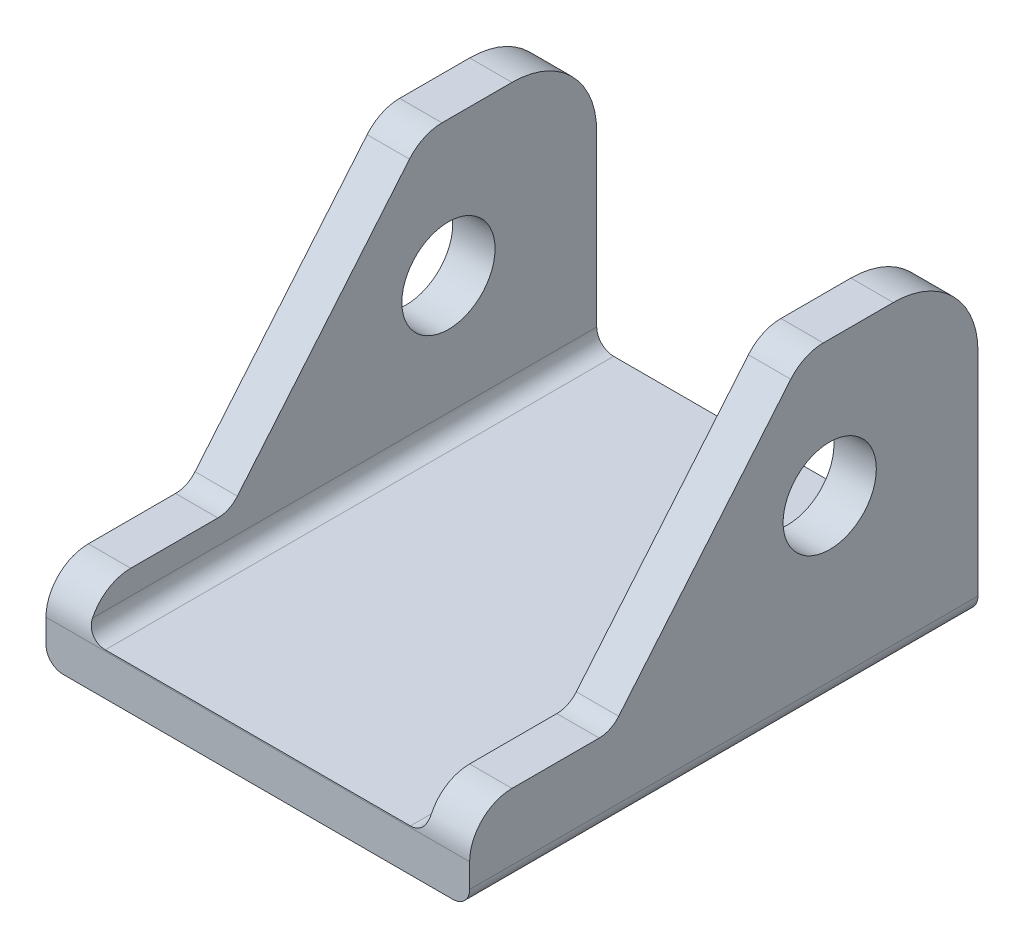
SolidWorks part; units mm, degrees
material "1.0490 (S275N)"
ref_plane "Front Plane" through (0, 0, 0) normal (0, 0, 1) x (1, 0, 0)
ref_plane "Top Plane" through (0, 0, 0) normal (0, 1, 0) x (1, 0, 0)
ref_plane "Right Plane" through (0, 0, 0) normal (1, 0, 0) x (0, 0, -1)
sketch "Sketch1" plane through (0, 0, 0) normal (0, 0, 1) x (1, 0, 0)
  line L0 (-86.9252, -8.2481) -> (-50.9252, -8.2481)
  line L1 (-88.9252, -6.2481) -> (-88.9252, 23.7519)
  line L2 (-48.9252, -6.2481) -> (-48.9252, 23.7519)
  line L3 (-93.9252, -11.2481) -> (-93.9252, 23.7519)
  line L4 (-91.9252, -13.2481) -> (-45.9252, -13.2481)
  line L5 (-43.9252, -11.2481) -> (-43.9252, 23.7519)
  line L6 (-88.9252, -8.2481) -> (-48.9252, -8.2481) construction
  line L7 (-88.9252, -8.2481) -> (-88.9252, 23.7519) construction
  line L8 (-48.9252, -8.2481) -> (-48.9252, 23.7519) construction
  line L9 (-93.9252, -13.2481) -> (-43.9252, -13.2481) construction
  line L10 (-43.9252, -13.2481) -> (-43.9252, 23.7519) construction
  line L11 (-93.9252, -13.2481) -> (-93.9252, 23.7519) construction
  line L12 (-93.9252, 23.7519) -> (-88.9252, 23.7519)
  line L13 (-48.9252, 23.7519) -> (-43.9252, 23.7519)
  arc A0 (-86.9252, -8.2481) -> (-88.9252, -6.2481) centre (-86.9252, -6.2481) cw
  arc A1 (-50.9252, -8.2481) -> (-48.9252, -6.2481) centre (-50.9252, -6.2481) ccw
  arc A2 (-45.9252, -13.2481) -> (-43.9252, -11.2481) centre (-45.9252, -11.2481) ccw
  arc A3 (-91.9252, -13.2481) -> (-93.9252, -11.2481) centre (-91.9252, -11.2481) cw
  dimension "D2" = 2
  dimension "D3" = 2
  dimension "D4" = 2
  dimension "D5" = 2
  dimension "D1" = 5
extrude "Boss-Extrude1" add sketch "Sketch1" along normal blind 60
hole_wizard "M10 Clearance Slot2" positions "Sketch4" profile "Sketch5" size "M10" standard "ISO" slot yes end condition through all
sketch "Sketch4" plane through (-43.9252, 0, 0) normal (1, 0, 0) x (0, 0, -1)
  line L0 (-60, -13.2481) -> (0, -13.2481) construction
  line L1 (0, -11.2481) -> (0, 23.7519) construction
  point P0 (-17.5, 7.7519)
  dimension "D1" = 21
  dimension "D2" = 17.5
sketch "Sketch5" plane through (-43.9252, 7.7519, 17.5) normal (0, 1, 0) x (0, 0, -1)
  line L0 (0, 0) -> (0, 50)
  line L1 (0, 50) -> (5.5, 50)
  line L2 (5.5, 50) -> (5.5, 0)
  line L5 (5.5, 0) -> (0, 0)
  line L11 (0, -6.35) -> (0, 107.95) construction
  dimension "Thru Hole Dia." = 11
  dimension "Thru Hole Depth" = 50
fillet "Fillet3" radius 10 1 edges at (-46.4252, 23.7519, 0)
fillet "Fillet4" radius 10 1 edges at (-91.4252, 23.7519, 0)
fillet "Fillet5" radius 10 1 edges at (-91.4252, 23.7519, 60)
fillet "Fillet6" radius 10 1 edges at (-46.4252, 23.7519, 60)
extrude "Cut-Extrude7" cut sketch "Sketch14" against normal through all and the other way through all
sketch "Sketch14" plane through (-93.9252, 454.8394, 464.6797) normal (-1, 0, 0) x (0, 1, 0)
  line L0 (-432.8802, 442.58) -> (-457.1734, 422.2676)
  line L2 (-458.249, 419.9661) -> (-458.249, 409.6797)
  line L4 (-431.0875, 446.4158) -> (-431.0875, 454.6797)
  line L5 (-463.249, 404.6797) -> (-466.0875, 404.6797)
  arc A0 (-457.1734, 422.2676) -> (-458.249, 419.9661) centre (-455.249, 419.9661) ccw
  arc A1 (-432.8802, 442.58) -> (-431.0875, 446.4158) centre (-436.0875, 446.4158) ccw
  arc A2 (-458.249, 409.6797) -> (-463.249, 404.6797) centre (-463.249, 409.6797) cw
  point P12 (-431.0875, 444.079)
  point P17 (-458.249, 404.6797)
